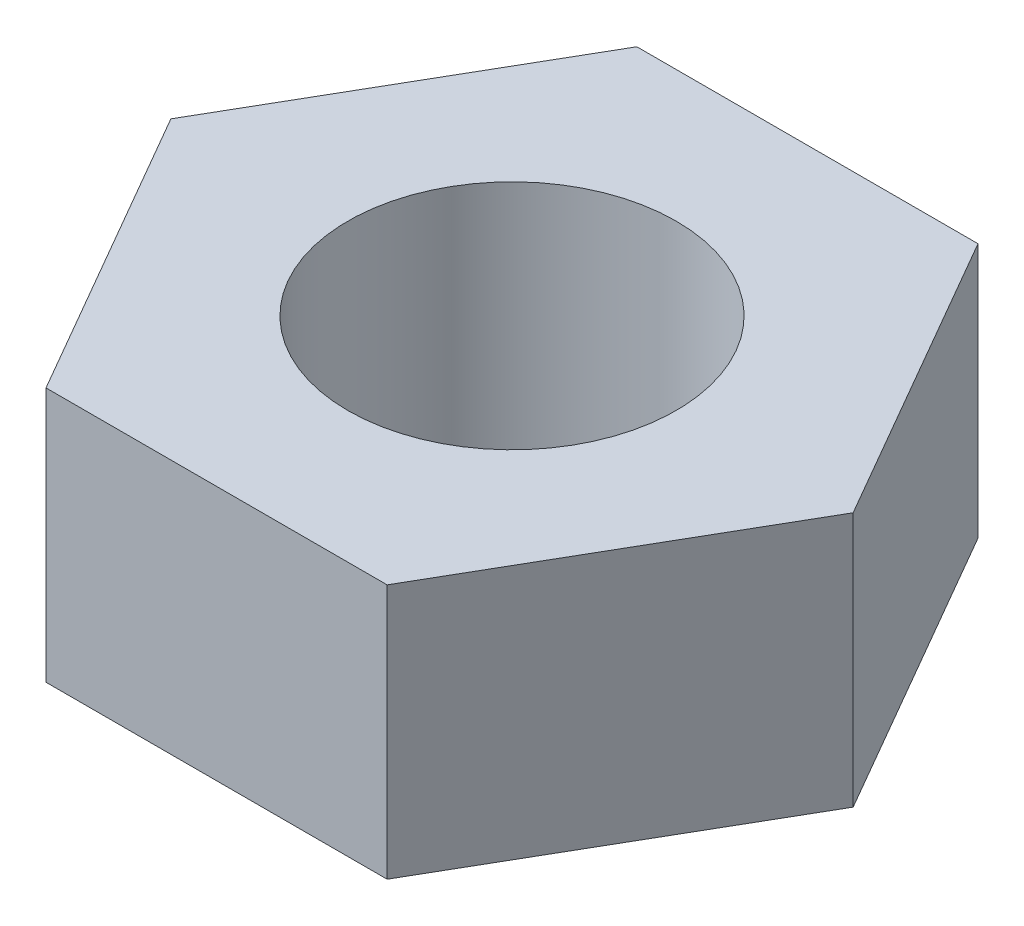
SolidWorks part; units mm, degrees
material "Plain Carbon Steel"
ref_plane "Front Plane" through (0, 0, 0) normal (0, 0, 1) x (1, 0, 0)
ref_plane "Top Plane" through (0, 0, 0) normal (0, 1, 0) x (1, 0, 0)
ref_plane "Right Plane" through (0, 0, 0) normal (1, 0, 0) x (0, 0, -1)
sketch "Sketch1" plane through (0, 0, 0) normal (0, 1, 0) x (1, 0, 0)
  line L1 (3.1177, 0) -> (1.5588, 2.7)
  line L2 (1.5588, 2.7) -> (-1.5588, 2.7)
  line L3 (-1.5588, 2.7) -> (-3.1177, 0)
  line L4 (-3.1177, 0) -> (-1.5588, -2.7)
  line L5 (-1.5588, -2.7) -> (1.5588, -2.7)
  line L6 (1.5588, -2.7) -> (3.1177, 0)
  circle A0 centre (0, 0) radius 2.7 construction
  dimension "D1" = 5.4
extrude "Boss-Extrude1" add sketch "Sketch1" along normal blind 2.33
sketch "Sketch2" plane through (0, 2.33, 0) normal (0, 1, 0) x (1, 0, 0)
  circle A0 centre (0, 0) radius 1.5
extrude "Cut-Extrude1" cut sketch "Sketch2" against normal blind 3
